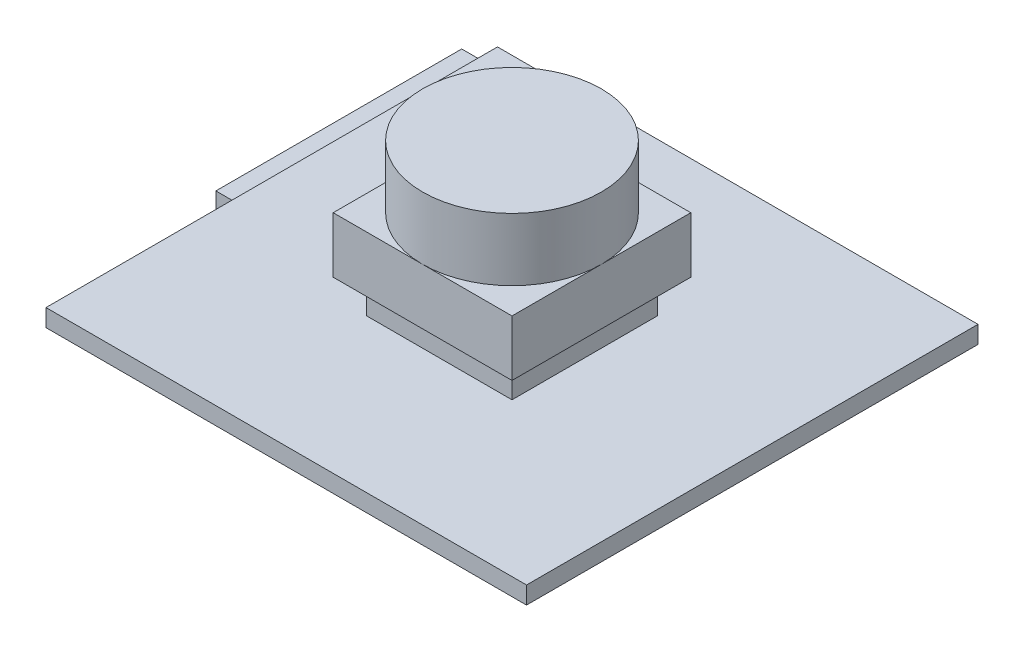
SolidWorks part; units mm, degrees
ref_plane "Спереди" through (0, 0, 0) normal (0, 0, 1) x (1, 0, 0)
ref_plane "Сверху" through (0, 0, 0) normal (0, 1, 0) x (1, 0, 0)
ref_plane "Справа" through (0, 0, 0) normal (1, 0, 0) x (0, 0, -1)
sketch "Эскиз1" plane through (0, 0, 0) normal (0, 1, 0) x (1, 0, 0)
  line L1 (-10.75, -10.1) -> (10.75, -10.1)
  line L2 (-10.75, -10.1) -> (-10.75, 10.1)
  line L3 (-10.75, 10.1) -> (10.75, 10.1)
  line L4 (10.75, -10.1) -> (10.75, 10.1)
  line L5 (-10.75, -10.1) -> (10.75, 10.1) construction
  line L6 (-10.75, 10.1) -> (10.75, -10.1) construction
  point P0 (0, 0)
  dimension "D1" = 21.5
  dimension "D2" = 20.2
extrude "Бобышка-Вытянуть1" add sketch "Эскиз1" along normal blind 0.78
sketch "Эскиз2" plane through (0, 0.78, 0) normal (0, 1, 0) x (1, 0, 0)
  line L1 (-3.25, -3.25) -> (3.25, -3.25)
  line L2 (-3.25, -3.25) -> (-3.25, 3.25)
  line L3 (-3.25, 3.25) -> (3.25, 3.25)
  line L4 (3.25, -3.25) -> (3.25, 3.25)
  line L5 (-3.25, -3.25) -> (3.25, 3.25) construction
  line L6 (-3.25, 3.25) -> (3.25, -3.25) construction
  point P0 (0, 0)
  dimension "D1" = 6.5
  dimension "D2" = 6.5
extrude "Бобышка-Вытянуть2" add sketch "Эскиз2" along normal blind 1.5
sketch "Эскиз3" plane through (0, 2.28, 0) normal (0, 1, 0) x (1, 0, 0)
  line L1 (-4, -4) -> (4, -4)
  line L2 (-4, -4) -> (-4, 4)
  line L3 (-4, 4) -> (4, 4)
  line L4 (4, -4) -> (4, 4)
  line L5 (-4, -4) -> (4, 4) construction
  line L6 (-4, 4) -> (4, -4) construction
  point P0 (0, 0)
  dimension "D1" = 8
  dimension "D2" = 8
extrude "Бобышка-Вытянуть3" add sketch "Эскиз3" along normal blind 2.5
sketch "Эскиз4" plane through (0, 4.78, 0) normal (0, 1, 0) x (1, 0, 0)
  circle A0 centre (0, 0) radius 4
extrude "Бобышка-Вытянуть4" add sketch "Эскиз4" along normal blind 2.8
sketch "Эскиз5" plane through (0, 0, 0) normal (0, -1, 0) x (1, 0, 0)
  line L1 (-12.25, -10) -> (3.25, -10)
  line L2 (-12.25, -10) -> (-12.25, 1)
  line L3 (-12.25, 1) -> (3.25, 1)
  line L4 (3.25, -10) -> (3.25, 1)
  line L5 (-10.75, -10.1) -> (-10.75, 10.1) construction
  line L6 (10.75, -10.1) -> (-10.75, -10.1) construction
  dimension "D1" = 15.5
  dimension "D2" = 11
  dimension "D3" = 1.5
  dimension "D4" = 0.1
extrude "Бобышка-Вытянуть5" add sketch "Эскиз5" along normal blind 2.28
